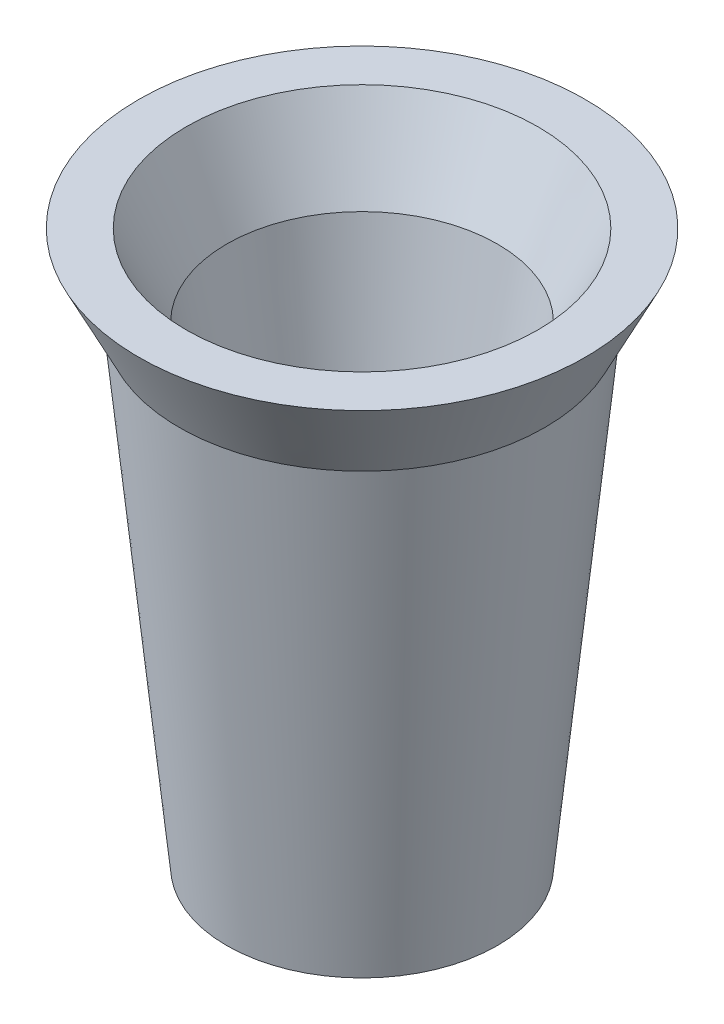
SolidWorks part; units mm, degrees
ref_plane "前视基准面" through (0, 0, 0) normal (0, 0, 1) x (1, 0, 0)
ref_plane "上视基准面" through (0, 0, 0) normal (0, 1, 0) x (1, 0, 0)
ref_plane "右视基准面" through (0, 0, 0) normal (1, 0, 0) x (0, 0, -1)
sketch "草图1" plane through (0, 0, 0) normal (0, 0, 1) x (1, 0, 0)
  line L0 (0, 174.5) -> (0, 0)
  line L1 (-17.5, 0) -> (17.5, 0)
  line L2 (-50, 174.5) -> (50, 174.5)
  line L3 (50, 174.5) -> (17.5, 0)
  line L4 (17.5, 0) -> (50, 0)
  line L5 (50, 0) -> (67.5, 174.5)
  line L6 (50, 174.5) -> (65, 204.5)
  line L7 (67.5, 174.5) -> (50, 174.5)
  line L8 (65, 204.5) -> (82.5, 204.5)
  line L9 (82.5, 204.5) -> (67.5, 174.5)
  line L10 (67.5, 174.5) -> (82.5, 174.5)
  line L11 (82.5, 174.5) -> (82.5, 204.5)
  point P6 (0, 0)
  point P9 (0, 174.5)
  dimension "D1" = 174.5
  dimension "D2" = 35
  dimension "D3" = 100
  dimension "D4" = 17.5
  dimension "D5" = 17.5
  dimension "D6" = 15
  dimension "D7" = 30
revolve "旋转1" add sketch "草图1" angle 360 about L0
